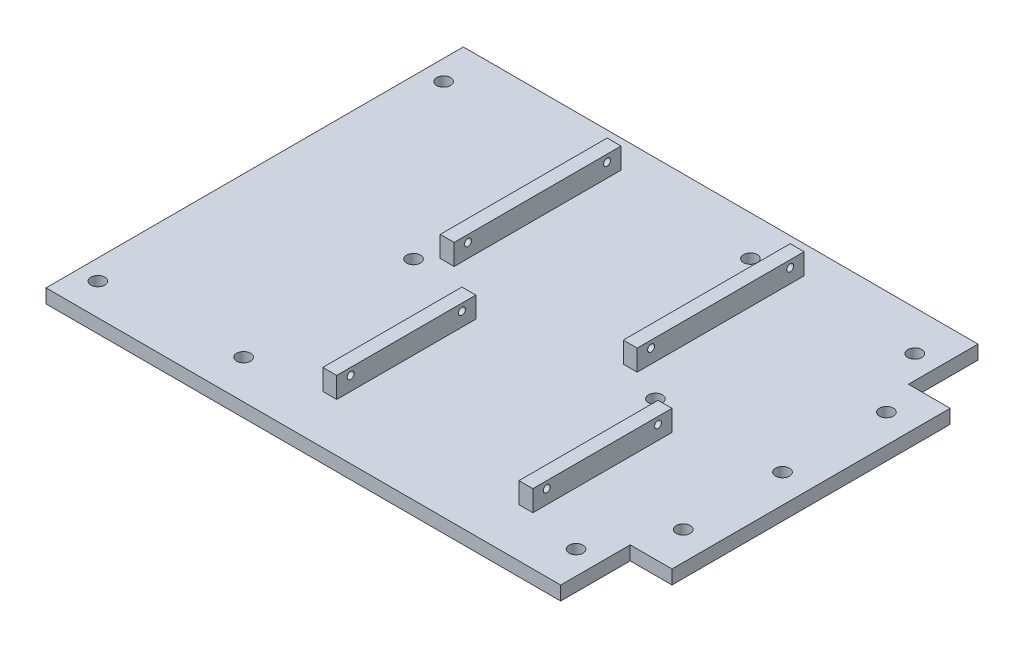
SolidWorks part; units mm, degrees
ref_plane "Front Plane" through (0, 0, 0) normal (0, 0, 1) x (1, 0, 0)
ref_plane "Top Plane" through (0, 0, 0) normal (0, 1, 0) x (1, 0, 0)
ref_plane "Right Plane" through (0, 0, 0) normal (1, 0, 0) x (0, 0, -1)
sketch "Sketch1" plane through (0, 0, 0) normal (0, 1, 0) x (1, 0, 0)
  line L1 (254, -190.5) -> (-254, -190.5)
  line L2 (254, -190.5) -> (254, 190.5)
  line L3 (254, 190.5) -> (-254, 190.5)
  line L4 (-254, -190.5) -> (-254, 190.5)
  line L5 (254, -190.5) -> (-254, 190.5) construction
  line L6 (254, 190.5) -> (-254, -190.5) construction
  point P0 (0, 0)
  dimension "D1" = 508
  dimension "D2" = 381
extrude "Boss-Extrude1" add sketch "Sketch1" along normal blind 12.7
sketch "Sketch5" plane through (0, 12.7, 0) normal (0, 1, 0) x (1, 0, 0)
  line L1 (133.35, -19.05) -> (146.05, -19.05)
  line L2 (133.35, -19.05) -> (133.35, -146.05)
  line L3 (133.35, -146.05) -> (146.05, -146.05)
  line L4 (146.05, -19.05) -> (146.05, -146.05)
  line L5 (133.35, -19.05) -> (146.05, -146.05) construction
  line L6 (133.35, -146.05) -> (146.05, -19.05) construction
  point P0 (139.7, -82.55)
  dimension "D1" = 127
  dimension "D2" = 12.7
extrude "Boss-Extrude2" add sketch "Sketch5" along normal blind 19.05
sketch "Sketch6" plane through (0, 12.7, 0) normal (0, 1, 0) x (1, 0, 0)
  line L1 (-45.72, -19.05) -> (-33.02, -19.05)
  line L2 (-45.72, -19.05) -> (-45.72, -146.05)
  line L3 (-45.72, -146.05) -> (-33.02, -146.05)
  line L4 (-33.02, -19.05) -> (-33.02, -146.05)
  line L5 (-45.72, -19.05) -> (-33.02, -146.05) construction
  line L6 (-45.72, -146.05) -> (-33.02, -19.05) construction
  point P0 (-39.37, -82.55)
  dimension "D1" = 127
  dimension "D2" = 12.7
extrude "Boss-Extrude3" add sketch "Sketch6" along normal blind 19.05
sketch "Sketch7" plane through (0, 12.7, 0) normal (0, 1, 0) x (1, 0, 0)
  line L1 (82.55, 12.7) -> (69.85, 12.7)
  line L2 (82.55, 12.7) -> (82.55, 165.1)
  line L3 (82.55, 165.1) -> (69.85, 165.1)
  line L4 (69.85, 12.7) -> (69.85, 165.1)
  line L5 (82.55, 12.7) -> (69.85, 165.1) construction
  line L6 (82.55, 165.1) -> (69.85, 12.7) construction
  line L7 (-84.582, 12.7) -> (-97.282, 12.7)
  line L8 (-84.582, 12.7) -> (-84.582, 165.1)
  line L9 (-84.582, 165.1) -> (-97.282, 165.1)
  line L10 (-97.282, 12.7) -> (-97.282, 165.1)
  line L11 (-84.582, 12.7) -> (-97.282, 165.1) construction
  line L12 (-84.582, 165.1) -> (-97.282, 12.7) construction
  point P0 (76.2, 88.9)
  point P5 (-90.932, 88.9)
  dimension "D1" = 152.4
  dimension "D2" = 12.7
  dimension "D3" = 152.4
  dimension "D4" = 12.7
extrude "Boss-Extrude6" add sketch "Sketch7" along normal blind 19.05
sketch "Sketch8" plane through (146.05, 0, 0) normal (1, 0, 0) x (0, 0, -1)
  circle A0 centre (-31.75, 25.4) radius 3.175
  circle A1 centre (-133.35, 25.4) radius 3.175
extrude "Cut-Extrude1" cut sketch "Sketch8" against normal through all both and the other way through all
sketch "Sketch9" plane through (82.55, 0, 0) normal (1, 0, 0) x (0, 0, -1)
  circle A0 centre (25.4, 25.4) radius 3.175
  circle A1 centre (152.4, 25.4) radius 3.175
  dimension "D1" = 6.35
extrude "Cut-Extrude2" cut sketch "Sketch9" against normal through all both and the other way through all
sketch "Sketch10" plane through (0, 12.7, 0) normal (0, 1, 0) x (1, 0, 0)
  line L1 (254, -190.5) -> (215.9, -190.5)
  line L2 (254, -190.5) -> (254, -127)
  line L3 (254, -127) -> (215.9, -127)
  line L4 (215.9, -190.5) -> (215.9, -127)
  dimension "D1" = 63.5
  dimension "D2" = 38.1
extrude "Cut-Extrude3" cut sketch "Sketch10" against normal through all
sketch "Sketch11" plane through (0, 12.7, 0) normal (0, 1, 0) x (1, 0, 0)
  line L1 (254, 190.5) -> (215.9, 190.5)
  line L2 (254, 190.5) -> (254, 127)
  line L3 (254, 127) -> (215.9, 127)
  line L4 (215.9, 190.5) -> (215.9, 127)
  dimension "D1" = 63.5
  dimension "D2" = 38.1
extrude "Cut-Extrude4" cut sketch "Sketch11" against normal through all
sketch "Sketch13" plane through (0, 12.7, 0) normal (0, 1, 0) x (1, 0, 0)
  circle A0 centre (227.9071, 0) radius 6.35
  circle A1 centre (111.9253, 0) radius 6.35
  circle A3 centre (-108.9695, 0) radius 6.35
  circle A4 centre (227.9071, -90.6734) radius 6.35
  circle A5 centre (227.9071, 94.9012) radius 6.35
  circle A6 centre (194.5481, 154.1515) radius 6.35
  circle A7 centre (194.5481, -155.1444) radius 6.35
  circle A8 centre (-235.6342, -161.4944) radius 6.35
  circle A9 centre (-235.6342, 154.1515) radius 6.35
  circle A10 centre (44.45, 154.1515) radius 6.35
  circle A11 centre (-108.9695, -155.1444) radius 6.35
extrude "Cut-Extrude5" cut sketch "Sketch13" against normal through all both and the other way through all
